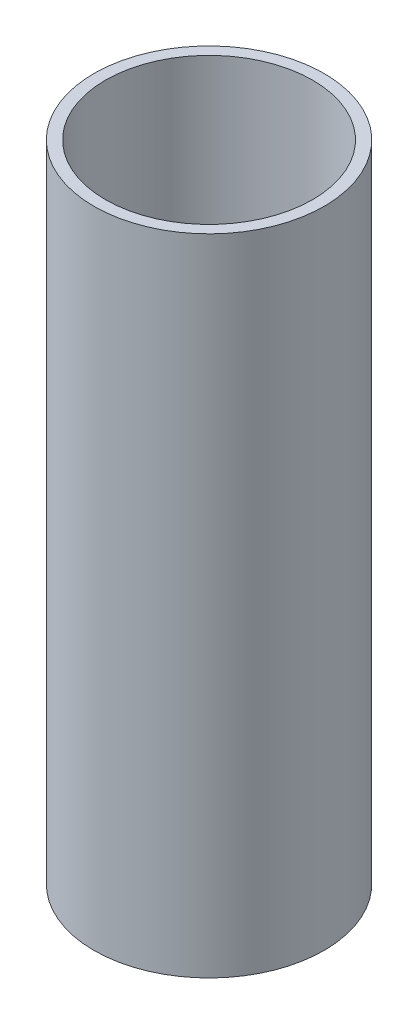
SolidWorks part; units mm, degrees
material "Alloy Steel"
ref_plane "Front Plane" through (0, 0, 0) normal (0, 0, 1) x (1, 0, 0)
ref_plane "Top Plane" through (0, 0, 0) normal (0, 1, 0) x (1, 0, 0)
ref_plane "Right Plane" through (0, 0, 0) normal (1, 0, 0) x (0, 0, -1)
sketch "BaseS" plane through (0, 0, 0) normal (0, 1, 0) x (1, 0, 0)
  circle A0 centre (0, 0) radius 4.5
  circle A1 centre (0, 0) radius 5
  dimension "InnerDia" = 9
  dimension "RefOuterDia" = 10
  dimension "Thickness" = 0.5
extrude "BASE" add sketch "BaseS" along normal mid plane 28
